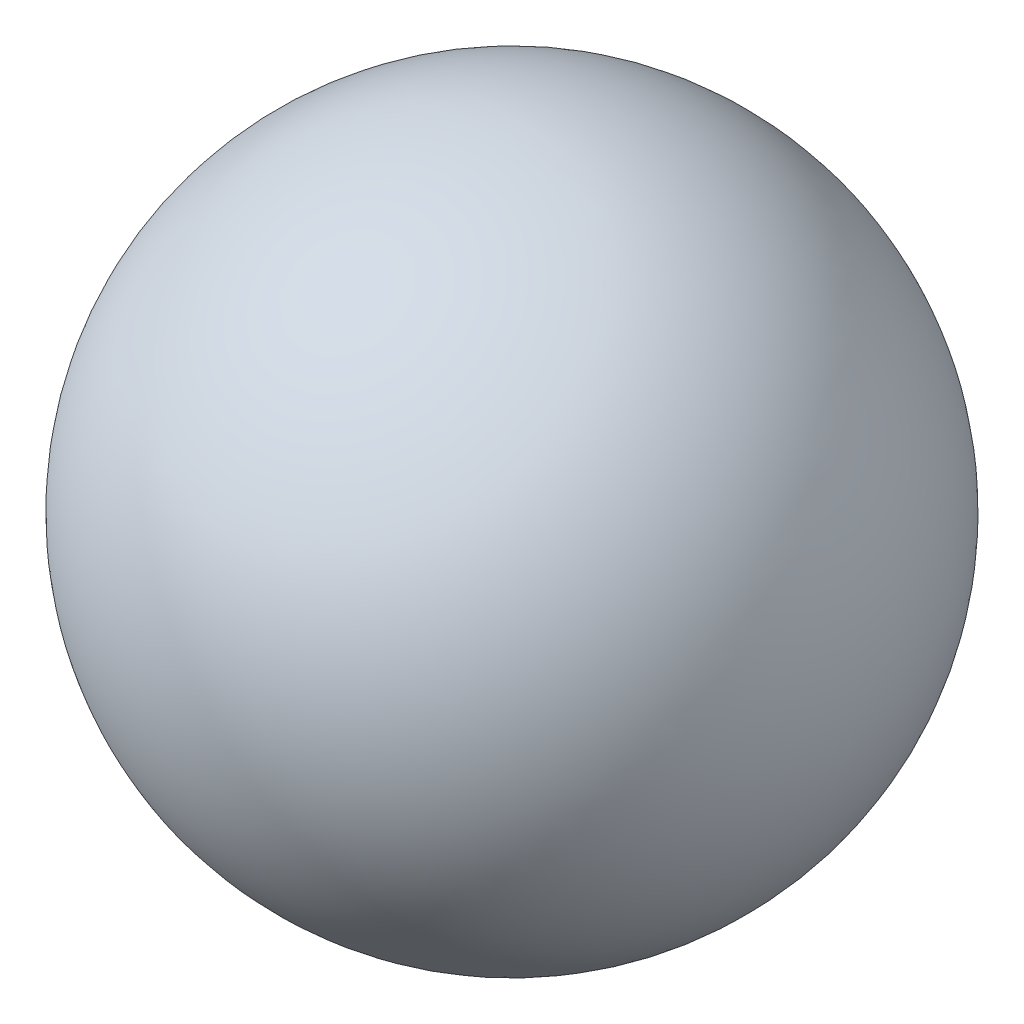
SolidWorks part; units mm, degrees
material "ABS PC"
ref_plane "Front Plane" through (0, 0, 0) normal (0, 0, 1) x (1, 0, 0)
ref_plane "Top Plane" through (0, 0, 0) normal (0, 1, 0) x (1, 0, 0)
ref_plane "Right Plane" through (0, 0, 0) normal (1, 0, 0) x (0, 0, -1)
sketch "Sketch1" plane through (0, 0, 0) normal (0, 1, 0) x (1, 0, 0)
  line L0 (0, 34.6995) -> (0, -26.1333) construction
  line L1 (0, 20.05) -> (0, 19.5125)
  line L2 (0, -20.05) -> (0, -19.5125)
  arc A0 (0, -20.05) -> (0, 20.05) centre (0, 0) ccw
  arc A1 (0, -19.5125) -> (0, 19.5125) centre (0, 0) ccw
  point P10 (0, 0)
  dimension "D1" = 40.1
  dimension "D2" = 39.025
revolve "Revolve1" add sketch "Sketch1" angle 360 about L0
